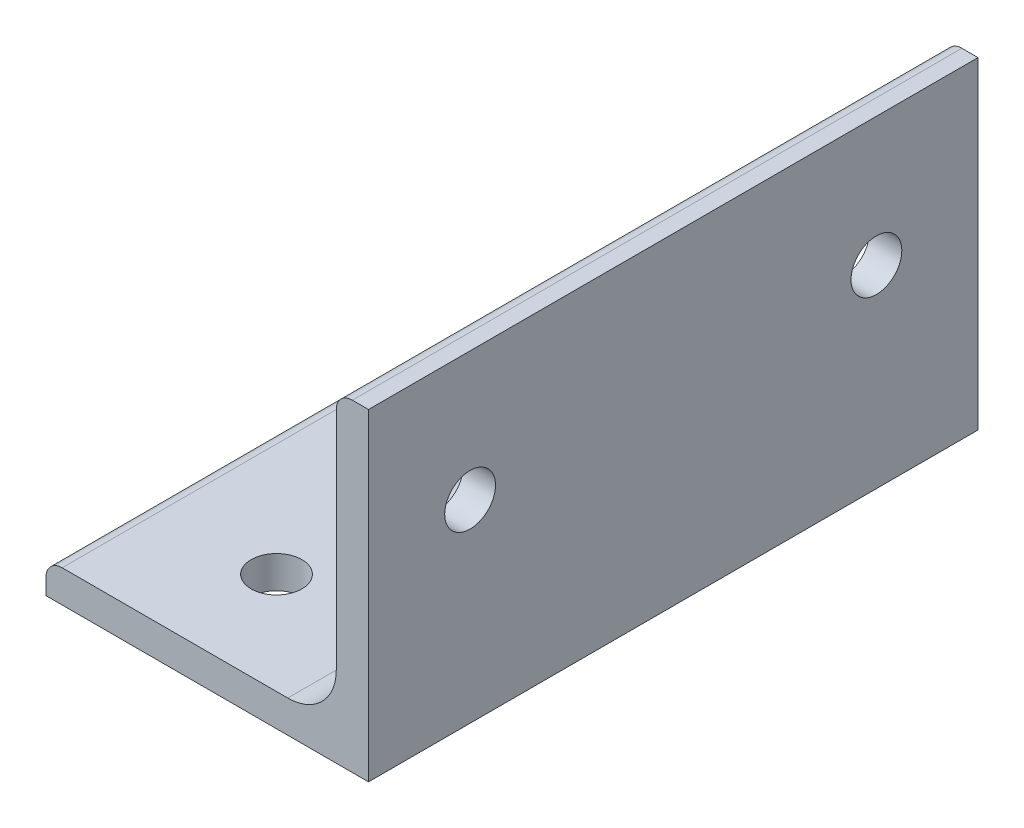
SolidWorks part; units mm, degrees
ref_plane "Front Plane" through (0, 0, 0) normal (0, 0, 1) x (1, 0, 0)
ref_plane "Top Plane" through (0, 0, 0) normal (0, 1, 0) x (1, 0, 0)
ref_plane "Right Plane" through (0, 0, 0) normal (1, 0, 0) x (0, 0, -1)
sketch "Sketch0" plane through (0, 0, 0) normal (0, 0, 1) x (1, 0, 0)
  line L0 (-15.875, -15.875) -> (15.875, -15.875)
  line L1 (15.875, -15.875) -> (15.875, 15.875)
  line L2 (15.875, 0) -> (0, 0) construction
  line L3 (0, 0) -> (0, -15.875) construction
  line L4 (12.7, -7.9248) -> (12.7, 15.875) construction
  line L5 (7.9248, -12.7) -> (-15.875, -12.7) construction
  arc A0 (12.7, -7.9248) -> (7.9248, -12.7) centre (7.9248, -7.9248) cw
  point P3 (11.3014, -11.3014)
  dimension "Inside Corner Radius" = 4.7752
  dimension "Outside Height" = 31.75
  dimension "Inside Height" = 28.575
  dimension "Inside Width" = 28.575
  dimension "Wall Thickness" = 3.175
  dimension "D1" = 3.175
  dimension "Outside Width" = 31.75
sketch "Sketch1" plane through (0, 0, 0) normal (1, 0, 0) x (0, 0, -1)
  line L0 (304.8, 0) -> (-304.8, 0)
  point P4 (0, 0)
  dimension "Length" = 609.6
sketch "Sketch2" plane through (0, 0, 0) normal (0, 0, 1) x (1, 0, 0)
  line L0 (-15.875, -15.875) -> (15.875, -15.875)
  line L1 (15.875, -15.875) -> (15.875, 15.875)
  line L2 (15.875, 15.875) -> (12.7, 15.875) construction
  line L3 (12.7, 14.2875) -> (12.7, -7.9248)
  line L4 (7.9248, -12.7) -> (-14.2875, -12.7)
  line L5 (-15.875, -15.875) -> (-15.875, -12.7) construction
  line L6 (14.2875, 15.875) -> (15.875, 15.875)
  line L7 (-15.875, -14.2875) -> (-15.875, -15.875)
  line L8 (15.875, 0) -> (0, 0) construction
  line L9 (0, 0) -> (0, -15.875) construction
  arc A0 (12.7, 14.2875) -> (14.2875, 15.875) centre (14.2875, 14.2875) cw
  arc A1 (-15.875, -14.2875) -> (-14.2875, -12.7) centre (-14.2875, -14.2875) cw
  arc A2 (12.7, -7.9248) -> (7.9248, -12.7) centre (7.9248, -7.9248) cw
  dimension "Inside Radius" = 4.7752
  dimension "Height" = 31.75
  dimension "Width" = 31.75
  dimension "Thickness" = 3.175
extrude "Boss-Extrude1" add sketch "Sketch2" along normal mid plane 609.6
sketch "Break Locations" plane through (0, 0, 0) normal (1, 0, 0) x (0, 0, -1)
  line L0 (-272.415, 0) -> (272.415, 0)
  line L1 (-304.8, -15.875) -> (-304.8, 15.875) construction
  line L2 (304.8, -15.875) -> (304.8, 15.875) construction
  point P0 (-277.8125, 0)
  point P1 (277.8125, 0)
  point P10 (0, 0)
  point P11 (272.415, 0)
  point P13 (-272.415, 0)
  dimension "D1" = 26.9875
  dimension "D2" = 26.9875
  dimension "D3" = 32.385
sketch "Sketch3" plane through (0, 0, -304.8) normal (0, 0, -1) x (-1, 0, 0)
  line L1 (-15.875, -15.875) -> (18.5395, -15.875)
  line L2 (-15.875, -15.875) -> (-15.875, 17.7829)
  line L3 (-15.875, 17.7829) -> (18.5395, 17.7829)
  line L4 (18.5395, -15.875) -> (18.5395, 17.7829)
extrude "Cut-Extrude1" cut sketch "Sketch3" against normal offset from surface (549.6 mm away) 60 up to face at (3.7396, -3.7396, 304.8)
sketch "Sketch4" plane through (0, -12.7, 0) normal (0, 1, 0) x (1, 0, 0)
  line L0 (-14.2875, -244.8) -> (7.9248, -244.8) construction
  line L1 (7.9248, -304.8) -> (-14.2875, -304.8) construction
  circle A0 centre (-3.1813, -254.8) radius 2.5
  circle A1 centre (-3.1813, -294.8) radius 2.5
  point P4 (0, 0)
  point P5 (-3.1813, -244.8)
  point P6 (0, 0)
  dimension "D1" = 5
  dimension "D2" = 5
  dimension "D3" = 10
  dimension "D4" = 10
sketch "Sketch5" plane through (12.7, 0, 0) normal (-1, 0, 0) x (0, 0, 1)
  line L0 (244.8, -7.9248) -> (244.8, 14.2875) construction
  line L1 (304.8, 14.2875) -> (304.8, -7.9248) construction
  circle A2 centre (294.8, 3.1813) radius 2.5
  circle A3 centre (254.8, 3.1813) radius 2.5
  point P0 (226.4201, 0)
  point P3 (244.8, 3.1813)
  point P4 (0, 0)
  point P10 (0, 0)
  dimension "D1" = 5
  dimension "D2" = 5
  dimension "D3" = 10
  dimension "D4" = 10
extrude "Cut-Extrude2" cut sketch "Sketch5" against normal blind 101.6
extrude "Cut-Extrude3" cut sketch "Sketch4" against normal blind 101.6
equation "\"D1@Break Locations\" = .85 * \"Height@Sketch2\""
equation "\"D2@Break Locations\"=\"D1@Break Locations\""
equation "\"Thickness@Sketch2\"=\"wall thickness@sketch0\""
equation "\"Height@Sketch2\"=\"outside height@sketch0\""
equation "\"Width@Sketch2\"=\"outside width@sketch0\""
equation "\"Inside Radius@Sketch2\"=\"inside corner radius@sketch0\""
equation "\"Length@Boss-Extrude1\"=\"length@sketch1\""
equation "\"D3@Break Locations\"=\"D2@Break Locations\"*1.2"
equation "\"D1@Sketch0\"=\"Wall Thickness@Sketch0\""
equation "\"D2@Sketch4\"=\"D1@Sketch4\""
